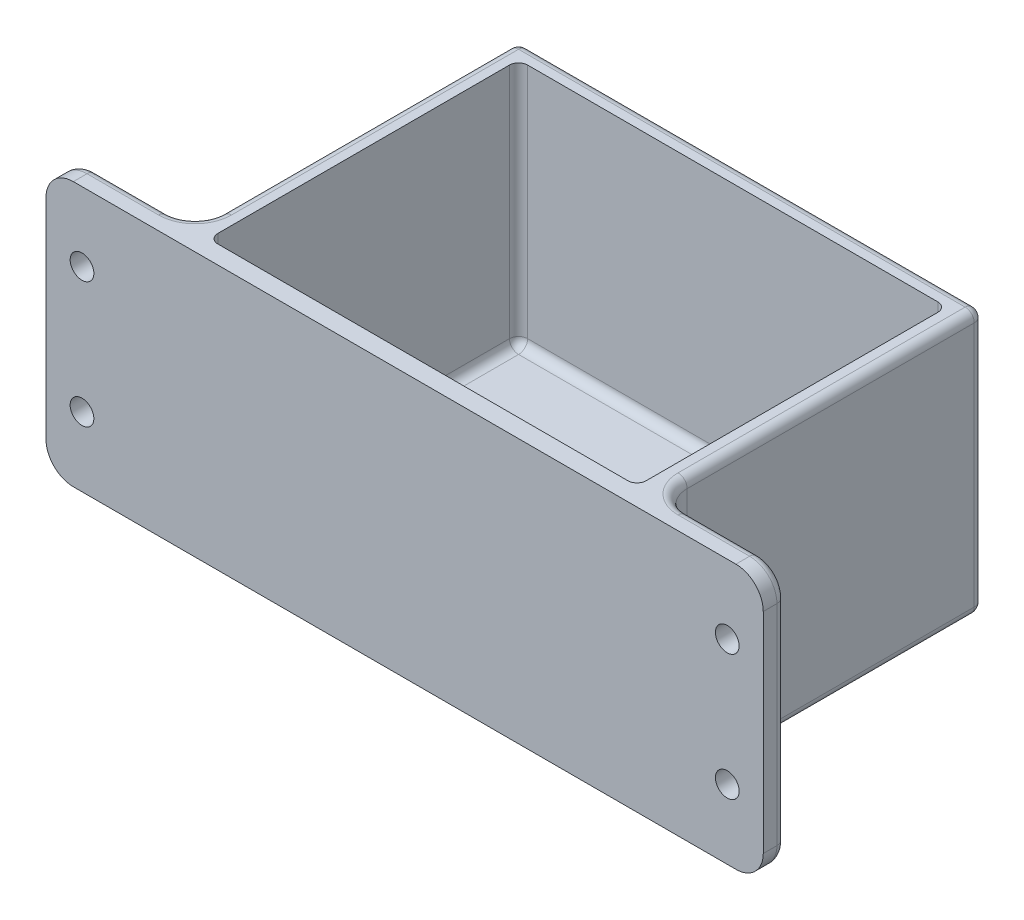
SolidWorks part; units mm, degrees
material "PLA"
ref_plane "Front Plane" through (0, 0, 0) normal (0, 0, 1) x (1, 0, 0)
ref_plane "Top Plane" through (0, 0, 0) normal (0, 1, 0) x (1, 0, 0)
ref_plane "Right Plane" through (0, 0, 0) normal (1, 0, 0) x (0, 0, -1)
sketch "Sketch1" plane through (0, 0, 0) normal (0, 1, 0) x (1, 0, 0)
  line L1 (-64.77, 48.26) -> (64.77, 48.26)
  line L2 (-64.77, 48.26) -> (-64.77, -48.26)
  line L3 (-64.77, -48.26) -> (64.77, -48.26)
  line L4 (64.77, 48.26) -> (64.77, -48.26)
  line L5 (-64.77, 48.26) -> (64.77, -48.26) construction
  line L6 (-64.77, -48.26) -> (64.77, 48.26) construction
  point P0 (0, 0)
  dimension "D1" = 129.54
  dimension "D2" = 96.52
extrude "Boss-Extrude1" add sketch "Sketch1" along normal blind 73.66
sketch "Sketch2" plane through (0, 73.66, 0) normal (0, 1, 0) x (1, 0, 0)
  line L1 (-59.69, 43.18) -> (59.69, 43.18)
  line L2 (-59.69, 43.18) -> (-59.69, -43.18)
  line L3 (-59.69, -43.18) -> (59.69, -43.18)
  line L4 (59.69, 43.18) -> (59.69, -43.18)
  line L5 (-59.69, 43.18) -> (59.69, -43.18) construction
  line L6 (-59.69, -43.18) -> (59.69, 43.18) construction
  point P0 (0, 0)
  dimension "D1" = 86.36
  dimension "D2" = 119.38
extrude "Cut-Extrude1" cut sketch "Sketch2" against normal blind 68.58
fillet "Fillet1" radius 2.54 8 edges at (59.69, 5.08, 0) (0, 5.08, 43.18) (-59.69, 39.37, 43.18) (59.69, 39.37, 43.18) (59.69, 39.37, -43.18) (-59.69, 5.08, 0) (0, 5.08, -43.18) (-59.69, 39.37, -43.18)
sketch "Sketch3" plane through (0, 0, 48.26) normal (0, 0, 1) x (1, 0, 0)
  line L0 (64.77, 36.83) -> (-64.77, 36.83) construction
  line L3 (0, -1000) -> (0, 49000) construction
  line L4 (-64.77, 73.66) -> (-64.77, 0)
  line L5 (-64.77, 0) -> (-99.949, 0)
  line L6 (-99.949, 0) -> (-99.949, 73.66)
  line L7 (-99.949, 73.66) -> (-64.77, 73.66)
  line L8 (99.949, 73.66) -> (64.77, 73.66)
  line L9 (99.949, 0) -> (99.949, 73.66)
  line L10 (64.77, 0) -> (99.949, 0)
  line L11 (64.77, 73.66) -> (64.77, 0)
  circle A0 centre (-89.916, 54.356) radius 3.302
  circle A2 centre (-89.916, 19.304) radius 3.302
  circle A3 centre (89.916, 19.304) radius 3.302
  circle A4 centre (89.916, 54.356) radius 3.302
  dimension "D2" = 6.604
  dimension "D5" = 6.604
  dimension "D1" = 35.052
  dimension "D3" = 89.916
  dimension "D4" = 199.898
extrude "Boss-Extrude2" add sketch "Sketch3" against normal blind 6.35
fillet "Fillet2" radius 7.62 2 edges at (-64.77, 36.83, 41.91) (64.77, 36.83, 41.91)
fillet "Fillet3" radius 7.62 2 edges at (-99.949, 73.66, 45.085) (-99.949, 0, 45.085)
fillet "Fillet4" radius 7.62 2 edges at (99.949, 73.66, 45.085) (99.949, 0, 45.085)
fillet "Fillet5" radius 2.54 22 edges at (-67.0018, 73.66, 39.6782) (-82.3595, 73.66, 41.91) (-97.7172, 71.4282, 41.91) (-99.949, 36.83, 41.91) (-97.7172, 2.2318, 41.91) (-82.3595, 0, 41.91) (-67.0018, 0, 39.6782) (67.0018, 0, 39.6782) (82.3595, 0, 41.91) (97.7172, 2.2318, 41.91) (99.949, 36.83, 41.91) (97.7172, 71.4282, 41.91) (82.3595, 73.66, 41.91) (67.0018, 73.66, 39.6782) (-64.77, 73.66, -6.985) (-64.77, 0, -6.985) (64.77, 0, -6.985) (64.77, 73.66, -6.985) (64.77, 36.83, -48.26) (0, 73.66, -48.26) (-64.77, 36.83, -48.26) (0, 0, -48.26)
